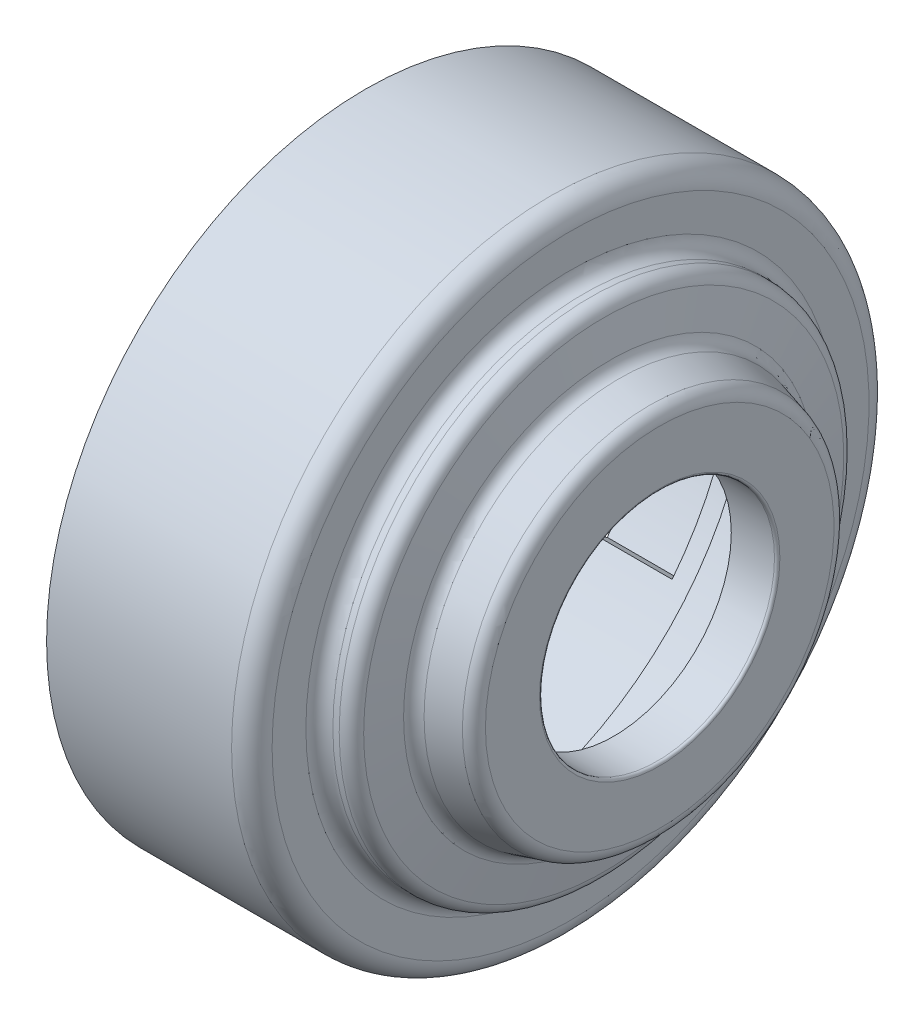
SolidWorks part; units mm, degrees
ref_plane "前视基准面" through (0, 0, 0) normal (0, 0, 1) x (1, 0, 0)
ref_plane "上视基准面" through (0, 0, 0) normal (0, 1, 0) x (1, 0, 0)
ref_plane "右视基准面" through (0, 0, 0) normal (1, 0, 0) x (0, 0, -1)
sketch "草图2" plane through (0, 0, 0) normal (0, 0, 1) x (1, 0, 0)
  line L0 (-36.9366, 0) -> (44.5849, 0) construction
  line L1 (0, 36.0368) -> (0, -37.1166) construction
  line L2 (-14, 22) -> (-6.9, 22)
  line L3 (-6.9, 22) -> (-6.9, 21.6)
  line L4 (-6.9, 21.6) -> (0, 21.6)
  line L5 (0, 21.6) -> (0, 17.4)
  line L6 (0, 17.4) -> (2.5, 17.4)
  line L9 (6.6, 12.75) -> (6.6, 9.4)
  line L10 (6.6, 9.4) -> (4.4, 9.4)
  line L11 (4.4, 9.4) -> (4.4, 8.7)
  line L12 (4.4, 8.7) -> (7.8, 8.7)
  line L13 (-14, 22) -> (-14, 23.6)
  line L14 (-14, 23.6) -> (1.2, 23.6)
  line L15 (1.2, 23.6) -> (1.2, 18.6)
  line L16 (1.2, 18.6) -> (3.5069, 18.6)
  line L19 (7.8, 13.6708) -> (7.8, 8.7)
  line L20 (2.5, 17.4) -> (3.1573, 13.6725)
  line L21 (3.5069, 18.6) -> (4.2063, 14.6337)
  line L22 (6.6, 12.75) -> (3.1573, 13.6725)
  line L23 (7.8, 13.6708) -> (4.2063, 14.6337)
  dimension "D1" = 44
  dimension "D2" = 0.4
  dimension "D3" = 7.1
  dimension "D4" = 14
  dimension "D5" = 34.8
  dimension "D6" = 2.5
  dimension "D7" = 18.8
  dimension "D8" = 0.7
  dimension "D9" = 4.4
  dimension "D10" = 2.2
  dimension "D11" = 25.5
  dimension "D12" = 47.2
  dimension "D13" = 2
  dimension "D14" = 1.2
  dimension "D15" = 10
  dimension "D16" = 105
  dimension "D17" = 1.2
  dimension "D18" = 1.2
  dimension "D19" = 1.2
  dimension "D20" = 1.6
  dimension "D21" = 1.2
revolve "旋转1" add sketch "草图2" angle 360 about L0
fillet "圆角1" radius 0.2 5 edges at (0, 0, 17.4) (0, 0, 21.6) (7.8, 0, 8.7) (2.5, 0, 17.4) (6.6, 0, 12.75)
fillet "圆角2" radius 1 4 edges at (1.2, 0, 18.6) (3.5069, 0, 18.6) (7.8, 0, 13.6708) (4.2063, 0, 14.6337)
fillet "圆角3" radius 1.5 2 edges at (1.2, 0, 23.6) (3.1573, 0, 13.6725)
sketch "草图3" plane through (-14, 0, 0) normal (-1, 0, 0) x (0, 0, 1)
  line L0 (0, 27.1942) -> (0, -25.474) construction
  line L1 (-27.7353, 0) -> (28.2343, 0) construction
  line L2 (-0.5, 22.6) -> (0.5, 22.6)
  line L3 (-0.5, 22.6) -> (-0.5, 21.9943)
  line L4 (0.5, 22.6) -> (0.5, 21.9943)
  circle A0 centre (0, 0) radius 22 construction
  arc A1 (0.5, 21.9943) -> (-0.5, 21.9943) centre (0, 0) ccw
  point P7 (0, 22)
  point P14 (0, 22.6)
  dimension "D1" = 1
  dimension "D2" = 0.6
extrude "切除-拉伸1" cut sketch "草图3" against normal blind 1
sketch "草图4" plane through (-14, 0, 0) normal (-1, 0, 0) x (0, 0, 1)
  line L0 (0, 29.159) -> (0, -31.1439) construction
  line L1 (-35.4917, 0) -> (32.6562, 0) construction
  line L2 (-3.25, 22.5672) -> (-3.25, 21.7586)
  line L3 (3.25, 22.5672) -> (3.25, 21.7586)
  circle A0 centre (0, 0) radius 22 construction
  arc A1 (3.25, 21.7586) -> (-3.25, 21.7586) centre (0, 0) ccw
  arc A2 (3.25, 22.5672) -> (-3.25, 22.5672) centre (0, 0) ccw
  dimension "D2" = 22.8
  dimension "D1" = 6.5
  dimension "D3" = 3.25
extrude "切除-拉伸2" cut sketch "草图4" against normal blind 5.5
sketch "草图5" plane through (0, 0, 0) normal (0, 0, 1) x (1, 0, 0)
  line L0 (16.6242, 0) -> (-23.7431, 0) construction
  line L1 (0, 27.01) -> (0, -27.8633) construction
  line L2 (-8.5, 22.8) -> (-8.5, 21.3419)
  line L3 (-8.5, 21.3419) -> (-10.7, 21.3419)
  line L4 (-10.7, 21.3419) -> (-10.7, 22.8)
  line L5 (-10.7, 22.8) -> (-8.5, 22.8)
  line L7 (-14, -0.1207) -> (-14, 29.419) construction
  line L8 (-14, 21.7586) -> (-14, -22) construction
  dimension "D1" = 3.3
  dimension "D2" = 2.2
  dimension "D3" = 45.6
revolve "切除-旋转1" cut sketch "草图5" angle 24 about L0
ref_plane "基准面1" through (0, 18, 0) normal (0, 1, 0) x (1, 0, 0)
sketch "草图6" plane through (0, 18, 0) normal (0, 1, 0) x (1, 0, 0)
  line L0 (16.0352, 0) -> (-25.287, 0) construction
  line L1 (-10.7, -8.9482) -> (-10.7, -3.25) construction
  line L2 (-10.7, -8.9482) -> (-10.7, -3.25)
  line L3 (-10.7, -3.25) -> (-10.7995, -8.9482)
  line L5 (-10.7, -8.9482) -> (-10.7995, -8.9482)
  dimension "D1" = 1
extrude "切除-拉伸3" cut sketch "草图6" along normal up to surface (2.9707 mm away)
pattern_circular "阵列(圆周)1" count 3 over 360 about axis through (0, 0, 0) along (1, 0, 0) of "切除-拉伸2", "切除-旋转1"
sketch "草图9" plane through (-10.7, 0, 0) normal (1, 0, 0) x (0, 0, -1)
  line L0 (-9.2736, 20.8288) -> (-8.9482, 20.098) construction
  line L1 (-8.9482, 20.9707) -> (-8.9482, 20.098) construction
  line L2 (-9.2736, 20.8288) -> (-8.9482, 20.098)
  line L3 (-8.9482, 20.9707) -> (-8.9482, 20.098)
  arc A0 (-8.9482, 20.9707) -> (-9.2736, 20.8288) centre (0, 0) ccw construction
  arc A1 (-8.9482, 20.9707) -> (-9.2736, 20.8288) centre (0, 0) ccw
extrude "切除-拉伸5" cut sketch "草图9" against normal up to surface (0.0995 mm away)
pattern_circular "阵列(圆周)3" count 3 over 360 about axis through (0, 0, 0) along (1, 0, 0) of "切除-拉伸3"
sketch "草图10" plane through (-10.7, 0, 0) normal (1, 0, 0) x (0, 0, -1)
  line L2 (22.6751, -2.3832) -> (21.8795, -2.2996)
  line L3 (21.8795, -2.2996) -> (22.6352, -2.736)
  line L4 (22.6751, -2.3832) -> (21.8795, -2.2996)
  line L5 (21.8795, -2.2996) -> (22.6352, -2.736)
  arc A1 (22.6352, -2.736) -> (22.6751, -2.3832) centre (0, 0) ccw
  arc A2 (22.6352, -2.736) -> (22.6751, -2.3832) centre (0, 0) ccw
  dimension "D1" = 0
extrude "切除-拉伸6" cut sketch "草图10" against normal up to surface (0.0995 mm away)
sketch "草图11" plane through (-10.7, 0, 0) normal (1, 0, 0) x (0, 0, -1)
  line L2 (-13.4015, -18.4456) -> (-12.9313, -17.7984)
  line L3 (-12.9313, -17.7984) -> (-13.687, -18.2347)
  line L4 (-13.4015, -18.4456) -> (-12.9313, -17.7984)
  line L5 (-12.9313, -17.7984) -> (-13.687, -18.2347)
  arc A1 (-13.687, -18.2347) -> (-13.4015, -18.4456) centre (0, 0) ccw
  arc A2 (-13.687, -18.2347) -> (-13.4015, -18.4456) centre (0, 0) ccw
  dimension "D1" = 0
extrude "切除-拉伸7" cut sketch "草图11" against normal up to surface (0.0995 mm away)
